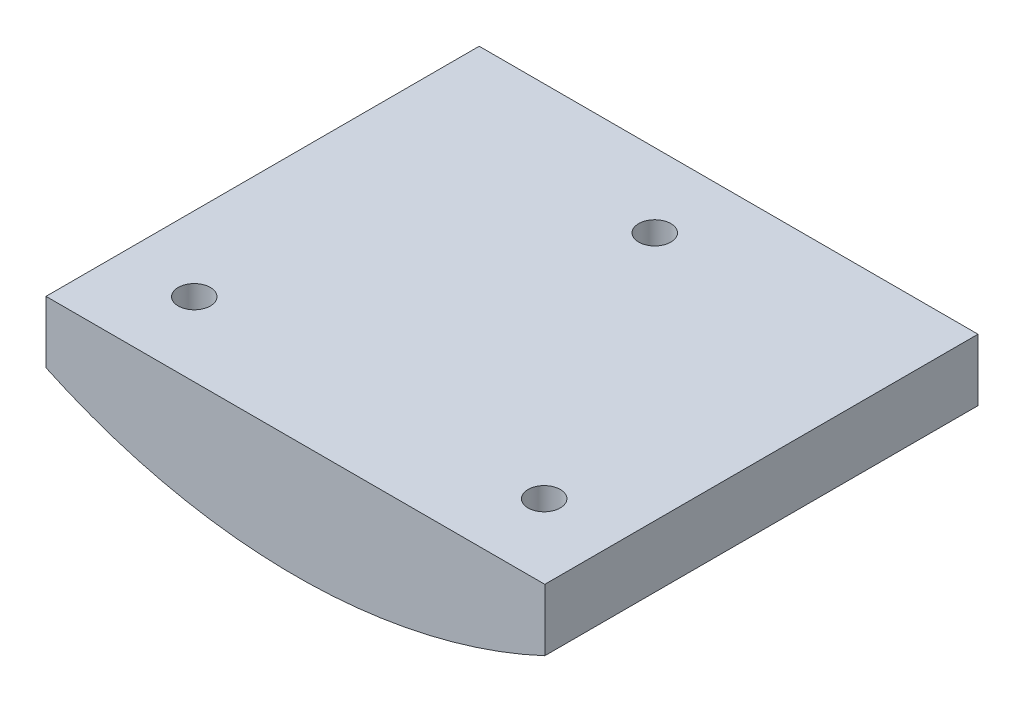
SolidWorks part; units mm, degrees
ref_plane "Front Plane" through (0, 0, 0) normal (0, 0, 1) x (1, 0, 0)
ref_plane "Top Plane" through (0, 0, 0) normal (0, 1, 0) x (1, 0, 0)
ref_plane "Right Plane" through (0, 0, 0) normal (1, 0, 0) x (0, 0, -1)
sketch "Sketch1" plane through (0, 0, 0) normal (0, 1, 0) x (1, 0, 0)
  line L1 (-25.5905, -22.225) -> (25.5905, -22.225)
  line L2 (-25.5905, -22.225) -> (-25.5905, 22.225)
  line L3 (-25.5905, 22.225) -> (25.5905, 22.225)
  line L4 (25.5905, -22.225) -> (25.5905, 22.225)
  line L5 (-25.5905, -22.225) -> (25.5905, 22.225) construction
  line L6 (-25.5905, 22.225) -> (25.5905, -22.225) construction
  point P0 (0, 0)
  dimension "D1" = 44.45
  dimension "D2" = 51.181
extrude "Boss-Extrude1" add sketch "Sketch1" along normal blind 6.35
sketch "Sketch2" plane through (0, 0, 22.225) normal (0, 0, 1) x (1, 0, 0)
  line L0 (-25.5905, 0) -> (25.5905, 0)
  arc A0 (-25.5905, 0) -> (25.5905, 0) centre (0, 54.6281) ccw
  dimension "D1" = 60.325
extrude "Boss-Extrude2" add sketch "Sketch2" against normal up to surface (44.45 mm away) up to face at (0, 3.175, -22.225)
sketch "Sketch3" plane through (0, 6.35, 0) normal (0, 1, 0) x (1, 0, 0)
  line L2 (0, 0) -> (0, 14.65) construction
  line L3 (17.95, -14.65) -> (17.95, -22.225) construction
  line L4 (-25.5905, -22.225) -> (25.5905, -22.225) construction
  line L5 (0, 14.65) -> (0, 22.225) construction
  line L6 (25.5905, 22.225) -> (-25.5905, 22.225) construction
  point P0 (-17.95, -14.65)
  point P1 (0, 14.65)
  point P2 (17.95, -14.65)
  dimension "D3" = 17.95
  dimension "D4" = 29.3
hole_wizard "M4x0.7 Tapped Hole1" positions "Sketch5" profile "Sketch4" tap size "M4x0.7" standard "ANSI Metric" end condition through all
sketch "Sketch5" plane through (0, 6.35, 0) normal (0, 1, 0) x (1, 0, 0)
  point P0 (0, 14.65)
  point P3 (-17.95, -14.65)
  point P6 (17.95, -14.65)
sketch "Sketch4" plane through (0, 6.35, -14.65) normal (1, 0, 0) x (0, 0, 1)
  line L0 (0, 0) -> (0, 12.0469)
  line L1 (0, 12.0469) -> (1.65, 12.0469)
  line L2 (1.65, 12.0469) -> (1.65, 0)
  line L5 (1.65, 0) -> (0, 0)
  line L11 (0, -6.35) -> (0, 107.95) construction
  dimension "Thru Tap Drill Dia." = 3.3
  dimension "Thru Tap Drill Depth" = 12.0469
cosmetic thread "Hole Thread1" parameters "D2"=4
cosmetic thread "Hole Thread2" parameters "D2"=4
cosmetic thread "Hole Thread3" parameters "D2"=4
